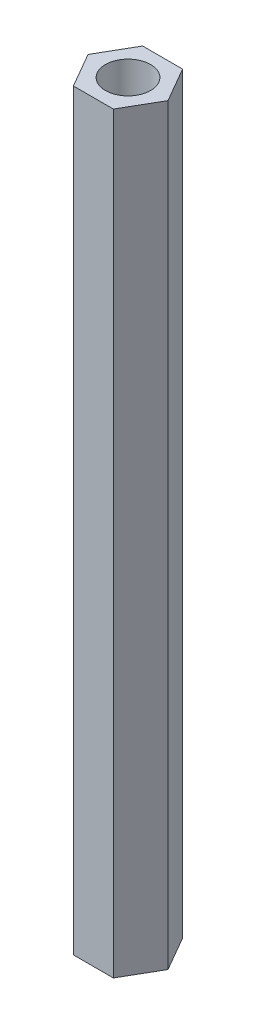
SolidWorks part; units mm, degrees
ref_plane "前视基准面" through (0, 0, 0) normal (0, 0, 1) x (1, 0, 0)
ref_plane "上视基准面" through (0, 0, 0) normal (0, 1, 0) x (1, 0, 0)
ref_plane "右视基准面" through (0, 0, 0) normal (1, 0, 0) x (0, 0, -1)
sketch "草图1" plane through (0, 0, 0) normal (0, 1, 0) x (1, 0, 0)
  line L1 (2.6558, 0) -> (1.3279, 2.3)
  line L2 (1.3279, 2.3) -> (-1.3279, 2.3)
  line L3 (-1.3279, 2.3) -> (-2.6558, 0)
  line L4 (-2.6558, 0) -> (-1.3279, -2.3)
  line L5 (-1.3279, -2.3) -> (1.3279, -2.3)
  line L6 (1.3279, -2.3) -> (2.6558, 0)
  circle A0 centre (0, 0) radius 2.3 construction
  circle A1 centre (0, 0) radius 1.5
  dimension "D2" = 3
  dimension "D1" = 4.6
extrude "凸台-拉伸1" add sketch "草图1" along normal blind 50
